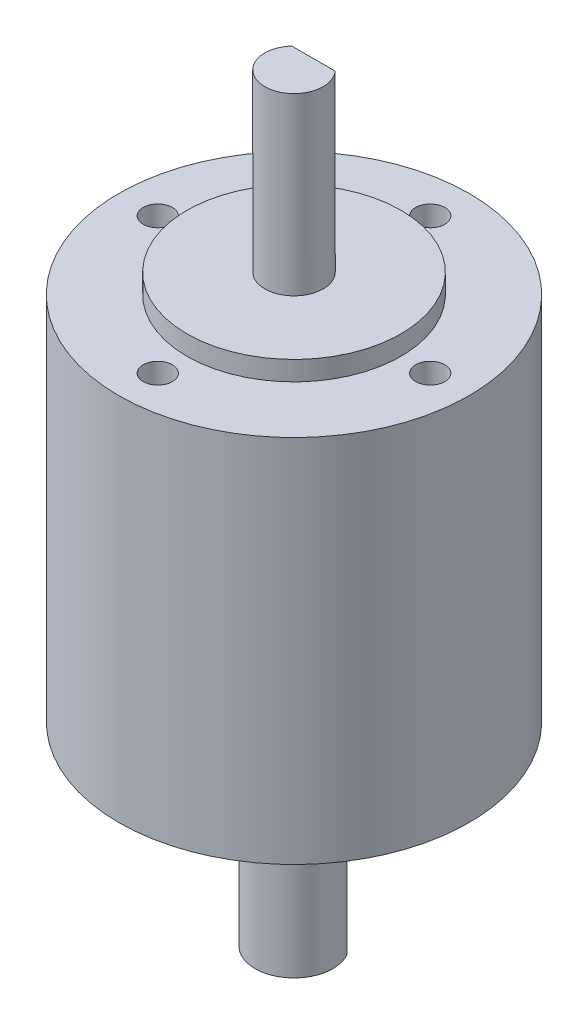
SolidWorks part; units mm, degrees
ref_plane "前视基准面" through (0, 0, 0) normal (0, 0, 1) x (1, 0, 0)
ref_plane "上视基准面" through (0, 0, 0) normal (0, 1, 0) x (1, 0, 0)
ref_plane "右视基准面" through (0, 0, 0) normal (1, 0, 0) x (0, 0, -1)
other "Configuration Table"
sketch "草图1" plane through (0, 0, 0) normal (0, 1, 0) x (1, 0, 0)
  circle A0 centre (0, 0) radius 18
  dimension "D1" = 36
extrude "凸台-拉伸1" add sketch "草图1" along normal blind 38
sketch "草图2" plane through (0, 38, 0) normal (0, 1, 0) x (1, 0, 0)
  circle A0 centre (0, 0) radius 11
  dimension "D1" = 22
extrude "凸台-拉伸2" add sketch "草图2" along normal blind 2
sketch "草图3" plane through (0, 0, 0) normal (0, -1, 0) x (1, 0, 0)
  circle A0 centre (0, 0) radius 11
  dimension "D1" = 22
extrude "凸台-拉伸3" add sketch "草图3" along normal blind 2
sketch "草图4" plane through (0, -2, 0) normal (0, -1, 0) x (1, 0, 0)
  circle A0 centre (0, 0) radius 4
  dimension "D1" = 8
extrude "凸台-拉伸4" add sketch "草图4" along normal blind 18
sketch "草图5" plane through (0, 40, 0) normal (0, 1, 0) x (1, 0, 0)
  circle A0 centre (0, 0) radius 3
  dimension "D1" = 6
extrude "凸台-拉伸5" add sketch "草图5" along normal blind 18
sketch "草图6" plane through (0, 58, 0) normal (0, 1, 0) x (1, 0, 0)
  line L1 (-4.794, 2) -> (4.4584, 2)
  line L2 (-4.794, 2) -> (-4.794, 6.6022)
  line L3 (-4.794, 6.6022) -> (4.4584, 6.6022)
  line L4 (4.4584, 2) -> (4.4584, 6.6022)
  dimension "D1" = 2
extrude "切除-拉伸1" cut sketch "草图6" against normal blind 15
sketch "草图7" plane through (0, -20, 0) normal (0, -1, 0) x (1, 0, 0)
  line L4 (4.4584, -2) -> (-4.794, -2)
  line L5 (4.4584, -6.6022) -> (4.4584, -2)
  line L6 (-4.794, -6.6022) -> (4.4584, -6.6022)
  line L7 (-4.794, -2) -> (-4.794, -6.6022)
  line L8 (4.4584, -2) -> (-4.794, -2)
  line L9 (4.4584, -6.6022) -> (4.4584, -2)
  line L10 (-4.794, -6.6022) -> (4.4584, -6.6022)
  line L11 (-4.794, -2) -> (-4.794, -6.6022)
  dimension "D1" = 0
extrude "切除-拉伸2" cut sketch "草图7" against normal blind 15
sketch "草图8" plane through (0, 0, 0) normal (0, -1, 0) x (1, 0, 0)
  line L0 (0, 0) -> (0, 14) construction
  circle A0 centre (0, 14) radius 1.5
  circle A1 centre (14, 0) radius 1.5
  circle A2 centre (0, -14) radius 1.5
  circle A3 centre (-14, 0) radius 1.5
  point P13 (0, 0)
  dimension "D1" = 3
  dimension "D2" = 14
  dimension "D3" = 4
extrude "切除-拉伸3" cut sketch "草图8" against normal blind 6
sketch "草图9" plane through (0, 38, 0) normal (0, 1, 0) x (1, 0, 0)
  circle A1 centre (-14, 0) radius 1.5
  circle A2 centre (-14, 0) radius 1.5
  circle A3 centre (0, 14) radius 1.5
  circle A4 centre (0, 14) radius 1.5
  circle A5 centre (14, 0) radius 1.5
  circle A6 centre (14, 0) radius 1.5
  circle A7 centre (0, -14) radius 1.5
  circle A8 centre (0, -14) radius 1.5
  dimension "D1" = 0
  dimension "D2" = 0
  dimension "D3" = 0
  dimension "D4" = 0
extrude "切除-拉伸4" cut sketch "草图9" against normal blind 6
